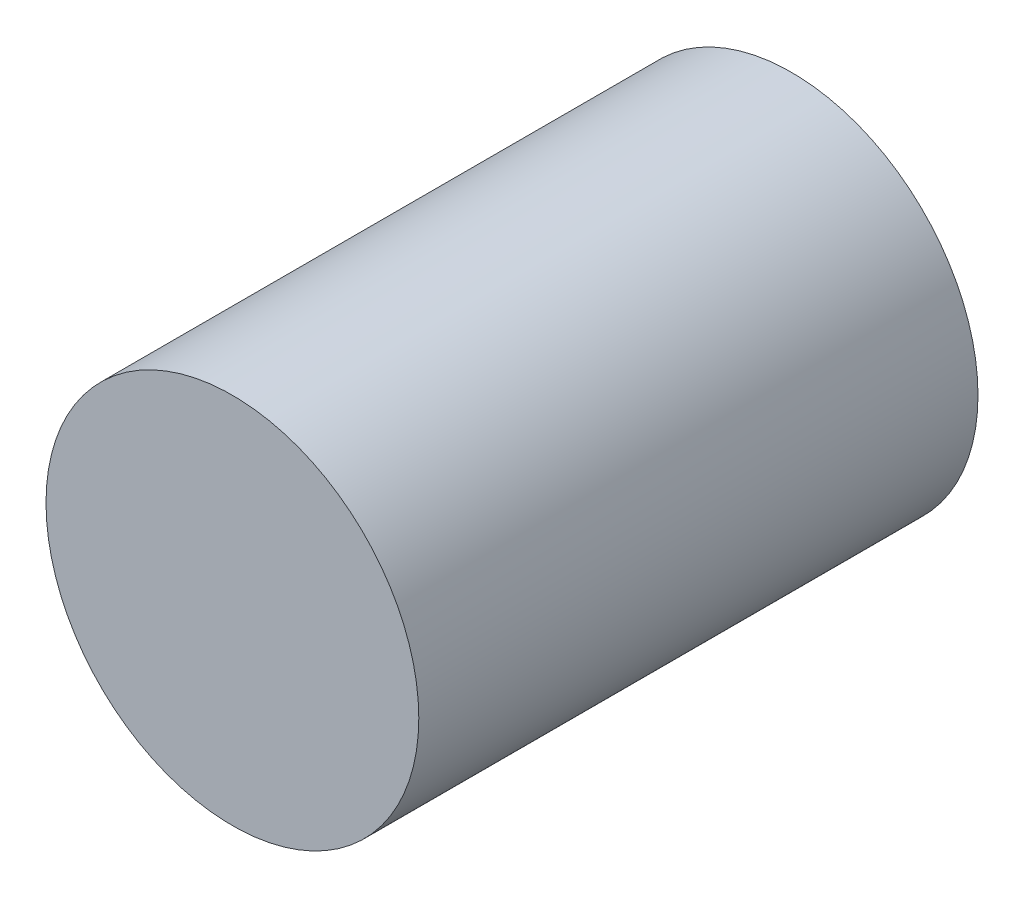
SolidWorks part; units mm, degrees
material "Nickel"
ref_plane "Front Plane" through (0, 0, 0) normal (0, 0, 1) x (1, 0, 0)
ref_plane "Top Plane" through (0, 0, 0) normal (0, 1, 0) x (1, 0, 0)
ref_plane "Right Plane" through (0, 0, 0) normal (1, 0, 0) x (0, 0, -1)
sketch "Sketch1" plane through (0, 0, 0) normal (0, 0, 1) x (1, 0, 0)
  circle A0 centre (0, 0) radius 10
  dimension "D1" = 20
extrude "Boss-Extrude1" add sketch "Sketch1" along normal blind 30
sketch "Sketch2" plane through (0, 0, 0) normal (0, 0, -1) x (-1, 0, 0)
  circle A0 centre (0, 0) radius 10
